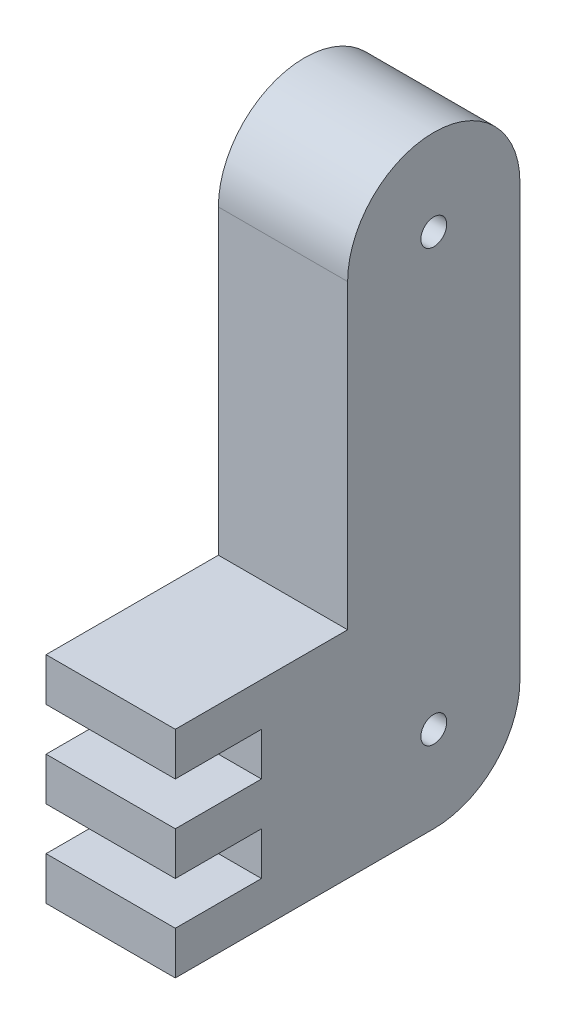
SolidWorks part; units mm, degrees
ref_plane "Front Plane" through (0, 0, 0) normal (0, 0, 1) x (1, 0, 0)
ref_plane "Top Plane" through (0, 0, 0) normal (0, 1, 0) x (1, 0, 0)
ref_plane "Right Plane" through (0, 0, 0) normal (1, 0, 0) x (0, 0, -1)
sketch "Sketch1" plane through (0, 0, 0) normal (1, 0, 0) x (0, 0, -1)
  line L1 (-10, 15) -> (-30, 15)
  line L3 (0, -10) -> (-30, -10)
  line L4 (-30, 15) -> (-30, -10)
  line L6 (-10, 50) -> (-10, 15)
  line L8 (10, 50) -> (10, 0)
  arc A0 (0, -10) -> (10, 0) centre (0, 0) ccw
  arc A1 (10, 50) -> (-10, 50) centre (0, 50) ccw
  circle A2 centre (0, 50) radius 1.5
  circle A3 centre (0, 0) radius 1.5
  dimension "D2" = 20
  dimension "D3" = 3
  dimension "D4" = 20
  dimension "D5" = 3
  dimension "D1" = 50
  dimension "D6" = 30
  dimension "D7" = 25
extrude "Boss-Extrude1" add sketch "Sketch1" along normal blind 15
sketch "Sketch2" plane through (15, 0, 0) normal (1, 0, 0) x (0, 0, -1)
  line L0 (-30, 15) -> (-30, -10) construction
  line L1 (-30, 10) -> (-20, 10)
  line L2 (-30, 10) -> (-30, 5)
  line L3 (-30, 5) -> (-20, 5)
  line L4 (-20, 10) -> (-20, 5)
  line L5 (-10, 15) -> (-30, 15) construction
  line L6 (-30, 0) -> (-20, 0)
  line L7 (-30, 0) -> (-30, -5)
  line L8 (-30, -5) -> (-20, -5)
  line L9 (-20, 0) -> (-20, -5)
  dimension "D1" = 10
  dimension "D2" = 5
  dimension "D3" = 5
  dimension "D4" = 5
  dimension "D5" = 5
  dimension "D6" = 10
extrude "Cut-Extrude1" cut sketch "Sketch2" against normal blind 15
